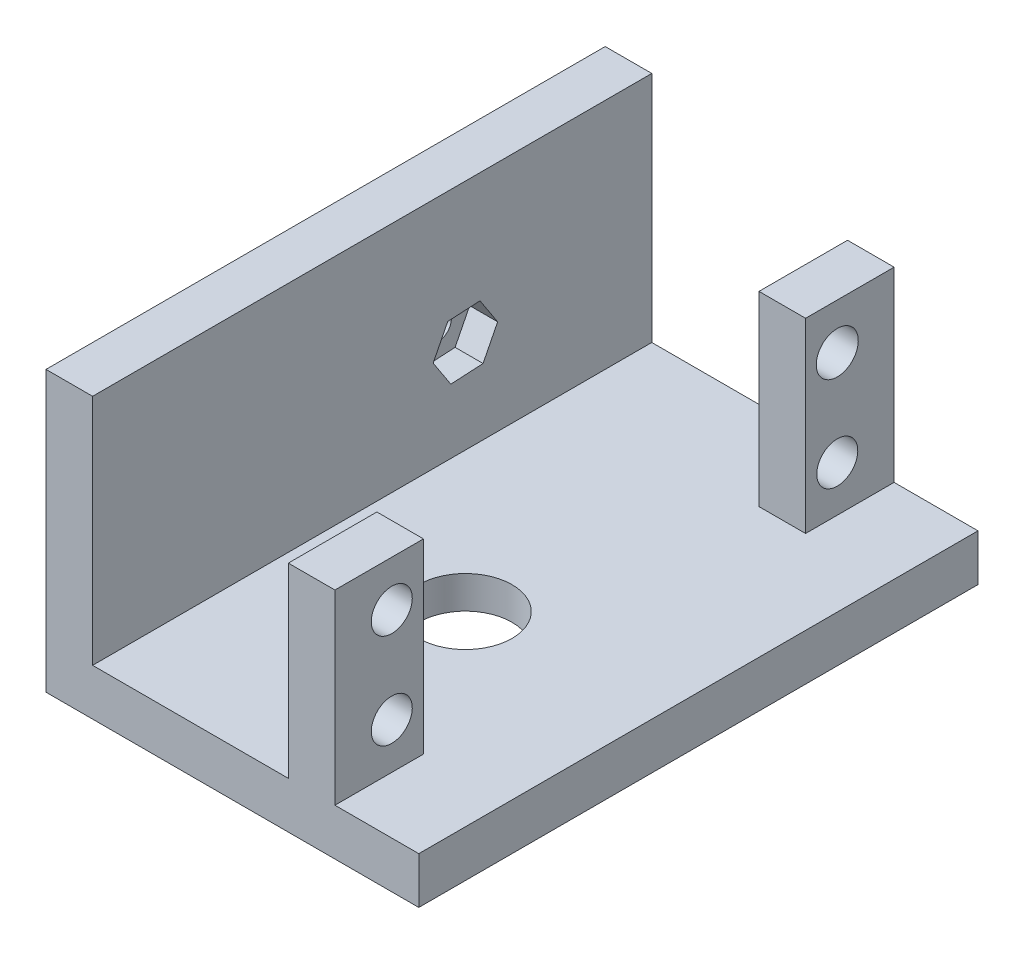
SolidWorks part; units mm, degrees
ref_plane "Alzado" through (0, 0, 0) normal (0, 0, 1) x (1, 0, 0)
ref_plane "Planta" through (0, 0, 0) normal (0, 1, 0) x (1, 0, 0)
ref_plane "Vista lateral" through (0, 0, 0) normal (1, 0, 0) x (0, 0, -1)
sketch "Croquis1" plane through (0, 0, 0) normal (0, 0, 1) x (1, 0, 0)
  line L0 (0, 0) -> (40, 0)
  line L1 (40, 0) -> (40, 5)
  line L2 (40, 5) -> (31, 5)
  line L3 (5, 5) -> (5, 30)
  line L4 (5, 30) -> (0, 30)
  line L5 (0, 30) -> (0, 0)
  line L6 (26, 5) -> (26, 25)
  line L7 (26, 25) -> (31, 25)
  line L8 (31, 25) -> (31, 5)
  line L9 (26, 5) -> (5, 5)
  dimension "D1" = 5
  dimension "D2" = 30
  dimension "D3" = 5
  dimension "D4" = 40
  dimension "D5" = 5
  dimension "D6" = 26
  dimension "D7" = 20
extrude "Saliente-Extruir1" add sketch "Croquis1" along normal blind 60
sketch "Croquis2" plane through (0, 25, 0) normal (0, 1, 0) x (1, 0, 0)
  line L1 (31, -50.5) -> (26, -50.5)
  line L2 (31, -50.5) -> (31, -9.5)
  line L3 (31, -9.5) -> (26, -9.5)
  line L4 (26, -50.5) -> (26, -9.5)
  line L8 (40, -60) -> (40, 0) construction
  line L9 (26, -60) -> (26, 0) construction
  line L11 (26, -9.5) -> (26, 0) construction
  line L12 (26, -60) -> (26, -50.5) construction
  dimension "D1" = 41
  dimension "D2" = 9
extrude "Cortar-Extruir1" cut sketch "Croquis2" against normal up to surface (20 mm away) up to face at (15.5, 5, 30)
sketch "Croquis4" plane through (0, 0, 0) normal (0, -1, 0) x (1, 0, 0)
  line L0 (20, 6.5117) -> (20, 63.4883) construction
  circle A2 centre (20, 35) radius 10.5
  dimension "D1" = 21
extrude "Cortar-Extruir3" cut sketch "Croquis4" against normal blind 1.5
sketch "Croquis5" plane through (0, 1.5, 0) normal (0, -1, 0) x (1, 0, 0)
  circle A0 centre (20, 35) radius 5
  dimension "D1" = 10
extrude "Cortar-Extruir4" cut sketch "Croquis5" against normal blind 51.5
sketch "Croquis7" plane through (31, 0, 0) normal (1, 0, 0) x (0, 0, -1)
  circle A0 centre (-53.9, 20.1) radius 2.2
  circle A1 centre (-53.9, 9.9) radius 2.2
  circle A2 centre (-6.1, 9.9) radius 2.2
  circle A3 centre (-6.1, 20.1) radius 2.2535
extrude "Cortar-Extruir5" cut sketch "Croquis7" against normal blind 10
sketch "Croquis8" plane through (0, 0, 0) normal (-1, 0, 0) x (0, 0, 1)
  circle A0 centre (20, 15) radius 1.5
extrude "Cortar-Extruir6" cut sketch "Croquis8" against normal blind 10
sketch "Croquis9" plane through (5, 0, 0) normal (1, 0, 0) x (0, 0, -1)
  line L1 (-18.436, 18.0909) -> (-21.8948, 17.8999)
  line L2 (-21.8948, 17.8999) -> (-23.4588, 14.809)
  line L3 (-23.4588, 14.809) -> (-21.564, 11.9091)
  line L4 (-21.564, 11.9091) -> (-18.1052, 12.1001)
  line L5 (-18.1052, 12.1001) -> (-16.5412, 15.191)
  line L6 (-16.5412, 15.191) -> (-18.436, 18.0909)
  circle A0 centre (-20, 15) radius 3 construction
  dimension "D1" = 6
extrude "Cortar-Extruir7" cut sketch "Croquis9" against normal blind 3
